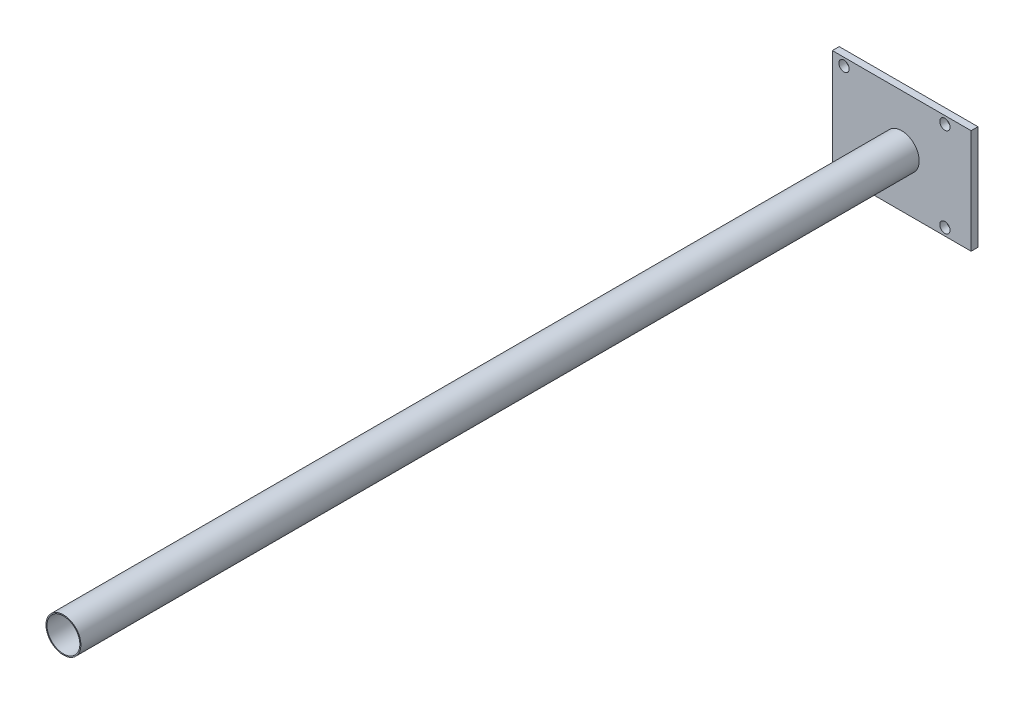
SolidWorks part; units mm, degrees
ref_plane "Front Plane" through (0, 0, 0) normal (0, 0, 1) x (1, 0, 0)
ref_plane "Top Plane" through (0, 0, 0) normal (0, 1, 0) x (1, 0, 0)
ref_plane "Right Plane" through (0, 0, 0) normal (1, 0, 0) x (0, 0, -1)
sketch "Sketch1" plane through (0, 0, 0) normal (0, 0, 1) x (1, 0, 0)
  line L1 (0, 0) -> (-202, 0)
  line L2 (0, 0) -> (0, 152)
  line L3 (0, 152) -> (-202, 152)
  line L4 (-202, 0) -> (-202, 152)
  circle A0 centre (-185, 141) radius 7.5
  circle A1 centre (-185, 11) radius 7.5
  circle A2 centre (-38.1779, 141) radius 7.5
  circle A3 centre (-38.1779, 11) radius 7.5
  point P13 (0, 0)
  point P14 (0, 0)
  point P15 (0, 0)
  point P16 (0, 0)
  dimension "D3" = 15
  dimension "D1" = 202
  dimension "D2" = 152
  dimension "D4" = 17
  dimension "D5" = 11
  dimension "D6" = 11
  dimension "D7" = 146.8221
extrude "Boss-Extrude1" add sketch "Sketch1" along normal blind 10
sketch "Sketch2" plane through (0, 0, 10) normal (0, 0, 1) x (1, 0, 0)
  line L0 (0, 152) -> (-202, 152) construction
  line L2 (0, 0) -> (0, 152) construction
  circle A0 centre (-101, 76) radius 23.9
  circle A1 centre (-101, 76) radius 25.4
  point P3 (0, 0)
  point P8 (-155.2513, 61.5459)
  point P11 (0, 76)
  dimension "D1" = 50.8
  dimension "D2" = 47.8
  dimension "D3" = 76
  dimension "D4" = 101
extrude "Boss-Extrude2" add sketch "Sketch2" along normal blind 1220
